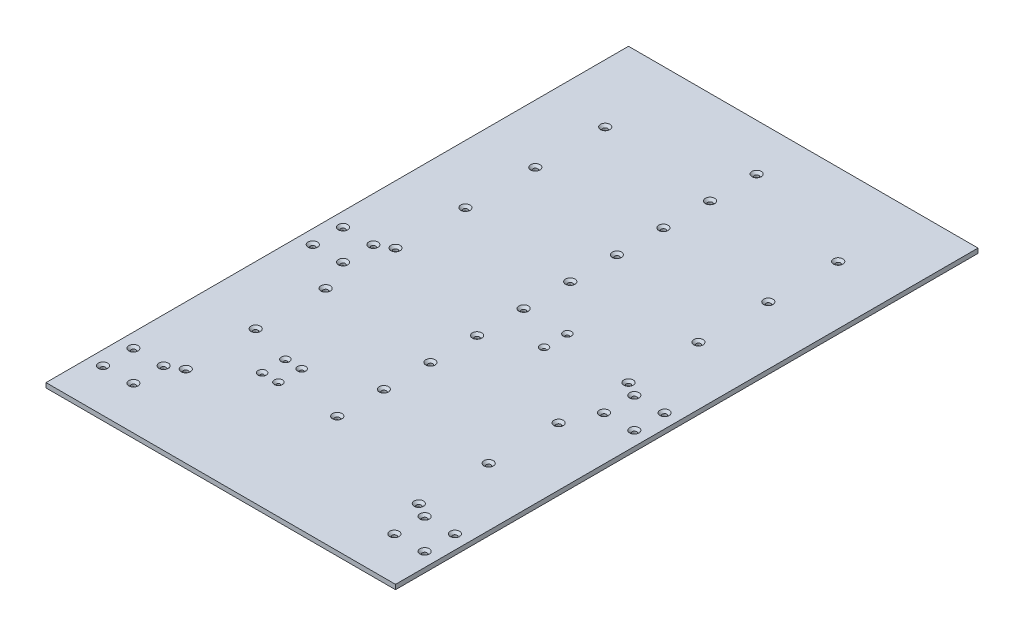
SolidWorks part; units mm, degrees
material "A-玻璃纤维"
ref_plane "前视基准面" through (0, 0, 0) normal (0, 0, 1) x (1, 0, 0)
ref_plane "上视基准面" through (0, 0, 0) normal (0, 1, 0) x (1, 0, 0)
ref_plane "右视基准面" through (0, 0, 0) normal (1, 0, 0) x (0, 0, -1)
sketch "草图1" plane through (0, 0, 0) normal (0, 1, 0) x (1, 0, 0)
  line L0 (0, 313.6998) -> (0, -340.7504) construction
  line L1 (-150, 250) -> (150, 250)
  line L2 (-150, 250) -> (-150, -250)
  line L3 (-150, -250) -> (150, -250)
  line L4 (150, 250) -> (150, -250)
  line L5 (-138, -187) -> (-112, -213) construction
  line L6 (-138, -7) -> (-112, -33) construction
  line L7 (138, -7) -> (112, -33) construction
  line L8 (138, -187) -> (112, -213) construction
  line L9 (-64.5, -130) -> (-50.5, -150) construction
  line L10 (-100, -180) -> (-100, -120) construction
  line L11 (0, -150) -> (0, -110) construction
  circle A0 centre (-138, -213) radius 2
  circle A1 centre (-112, -213) radius 2
  circle A2 centre (-138, -187) radius 2
  circle A3 centre (-112, -187) radius 2
  circle A4 centre (-112, -33) radius 2
  circle A5 centre (-138, -7) radius 2
  circle A6 centre (-138, -33) radius 2
  circle A7 centre (-112, -7) radius 2
  circle A8 centre (112, -7) radius 2
  circle A9 centre (138, -33) radius 2
  circle A10 centre (138, -7) radius 2
  circle A11 centre (112, -33) radius 2
  circle A12 centre (112, -187) radius 2
  circle A13 centre (138, -187) radius 2
  circle A14 centre (112, -213) radius 2
  circle A15 centre (138, -213) radius 2
  circle A16 centre (-64.5, -130) radius 1.5
  circle A17 centre (-50.5, -130) radius 1.5
  circle A18 centre (-64.5, -150) radius 1.5
  circle A19 centre (-50.5, -150) radius 1.5
  circle A20 centre (-100, -180) radius 2
  circle A21 centre (-100, -120) radius 2
  circle A22 centre (-100, -60) radius 2
  circle A23 centre (-100, 0) radius 2
  circle A24 centre (-100, 60) radius 2
  circle A25 centre (-100, 120) radius 2
  circle A26 centre (-100, 180) radius 2
  circle A27 centre (100, -120) radius 2
  circle A28 centre (100, 180) radius 2
  circle A29 centre (100, 120) radius 2
  circle A30 centre (100, 60) radius 2
  circle A31 centre (100, 0) radius 2
  circle A32 centre (100, -60) radius 2
  circle A33 centre (100, -180) radius 2
  circle A34 centre (0, -150) radius 2
  circle A35 centre (0, -110) radius 2
  circle A36 centre (0, -70) radius 2
  circle A37 centre (0, -30) radius 2
  circle A38 centre (0, 10) radius 2
  circle A39 centre (0, 50) radius 2
  circle A40 centre (0, 90) radius 2
  circle A41 centre (0, 130) radius 2
  circle A42 centre (0, 170) radius 2
  circle A43 centre (0, 210) radius 2
  circle A44 centre (37.5, -10) radius 1.5
  circle A45 centre (37.5, 10) radius 1.5
  point P4 (0, 250)
  point P6 (150, 0)
  point P17 (-125, -200)
  point P28 (-125, -20)
  point P51 (-57.5, -140)
  point P107 (0, 0)
  point P108 (0, 0)
  point P109 (0, 0)
  dimension "D3" = 4
  dimension "D4" = 125
  dimension "D11" = 3
  dimension "D18" = 4
  dimension "D22" = 4
  dimension "D26" = 3
  dimension "D1" = 500
  dimension "D2" = 300
  dimension "D5" = 50
  dimension "D6" = 26
  dimension "D7" = 26
  dimension "D8" = 26
  dimension "D9" = 26
  dimension "D10" = 180
  dimension "D12" = 14
  dimension "D13" = 20
  dimension "D14" = 57.5
  dimension "D15" = 110
  dimension "D16" = 50
  dimension "D17" = 70
  dimension "D20" = 60
  dimension "D21" = 400
  dimension "D24" = 40
  dimension "D25" = 150
  dimension "D27" = 20
  dimension "D28" = 112.5
  dimension "D29" = 260
  dimension "D19" = 7
  dimension "D23" = 10
extrude "凸台-拉伸1" add sketch "草图1" along normal blind 4
chamfer "倒角1" distance 2 angle 45 34 edges at (-100, 4, 182) (100, 4, 178) (100, 4, 118) (100, 4, 58) (100, 4, -2) (100, 4, -62) (100, 4, -122) (100, 4, -182) (-100, 4, -178) (-100, 4, -118) (-100, 4, -58) (-100, 4, 2) (-100, 4, 62) (-100, 4, 122) (138, 4, 185) (112, 4, 185) (112, 4, 211) (138, 4, 211) (138, 4, 31) (112, 4, 31) (112, 4, 5) (138, 4, 5) (-112, 4, 9) (-138, 4, 9) (-138, 4, 35) (-112, 4, 35) (-64.5, 4, 131.5) (-50.5, 4, 131.5) (-50.5, 4, 151.5) (-64.5, 4, 151.5) (-112, 4, 189) (-138, 4, 189) (-138, 4, 215) (-112, 4, 215)
chamfer "倒角2" distance 2 angle 45 12 edges at (0, 4, -208) (0, 4, -168) (0, 4, -128) (0, 4, -88) (0, 4, -48) (0, 4, -8) (0, 4, 32) (0, 4, 72) (0, 4, 112) (0, 4, 152) (37.5, 4, 11.5) (37.5, 4, -8.5)
